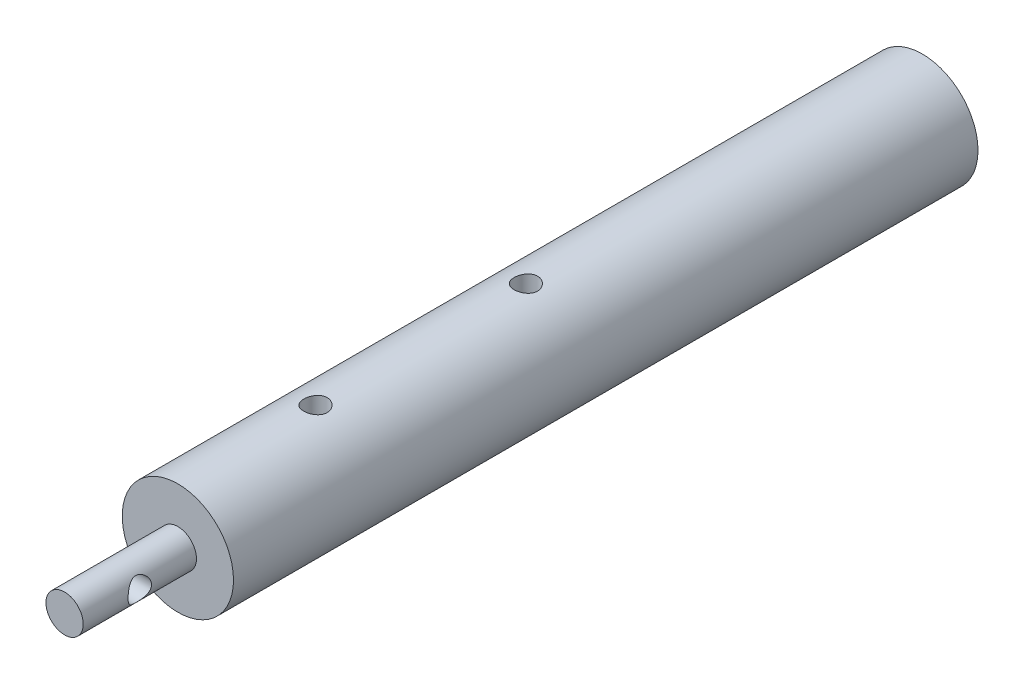
SolidWorks part; units mm, degrees
ref_plane "Front Plane" through (0, 0, 0) normal (0, 0, 1) x (1, 0, 0)
ref_plane "Top Plane" through (0, 0, 0) normal (0, 1, 0) x (1, 0, 0)
ref_plane "Right Plane" through (0, 0, 0) normal (1, 0, 0) x (0, 0, -1)
sketch "Sketch1" plane through (0, 0, 0) normal (0, 0, 1) x (1, 0, 0)
  circle A0 centre (0, 0) radius 8.7312
  dimension "D1" = 17.4625
extrude "Boss-Extrude1" add sketch "Sketch1" along normal blind 116.84
sketch "Sketch2" plane through (0, 0, 116.84) normal (0, 0, 1) x (1, 0, 0)
  circle A0 centre (0, 0) radius 2.921
  dimension "D1" = 5.842
extrude "Boss-Extrude2" add sketch "Sketch2" along normal blind 17.78
ref_plane "Plane1" through (0, 8.7312, 0) normal (0, 1, 0) x (1, 0, 0)
sketch "Sketch4" plane through (0, 8.7312, 0) normal (0, 1, 0) x (1, 0, 0)
  line L1 (-2.921, -134.62) -> (2.921, -134.62) construction
  circle A0 centre (0, -62.23) radius 1.8415
  circle A1 centre (0, -95.25) radius 1.8415
  dimension "D1" = 3.683
  dimension "D2" = 33.02
  dimension "D3" = 39.37
hole_wizard "#6-32 Tapped Hole1" positions "Sketch5" profile "Sketch6" tap size "#6-32" standard "ANSI Inch" end condition through all
sketch "Sketch5" plane through (0, 8.7312, 0) normal (0, 1, 0) x (1, 0, 0)
  point P0 (0, -62.23)
  point P3 (0, -95.25)
sketch "Sketch6" plane through (0, 8.7312, 62.23) normal (1, 0, 0) x (0, 0, 1)
  line L0 (0, 0) -> (0, 17.4625)
  line L1 (0, 17.4625) -> (1.3525, 17.4625)
  line L2 (1.3525, 17.4625) -> (1.3525, 0)
  line L5 (1.3525, 0) -> (0, 0)
  line L11 (0, -6.35) -> (0, 107.95) construction
  dimension "Thru Tap Drill Dia." = 2.7051
  dimension "Thru Tap Drill Depth" = 17.4625
cosmetic thread "Hole Thread1" parameters "D2"=3.5052
cosmetic thread "Hole Thread2" parameters "D2"=3.5052
ref_plane "Plane2" through (2.921, 0, 0) normal (1, 0, 0) x (0, 0, -1)
sketch "Sketch7" plane through (2.921, 0, 0) normal (1, 0, 0) x (0, 0, -1)
  line L1 (-134.62, 2.921) -> (-134.62, -2.921) construction
  circle A0 centre (-125.73, 0) radius 1.8415
  dimension "D1" = 3.683
  dimension "D2" = 8.89
hole_wizard "#6-32 Tapped Hole2" positions "Sketch8" profile "Sketch9" tap size "#6-32" standard "ANSI Inch" end condition through all
sketch "Sketch8" plane through (2.921, 0, 0) normal (1, 0, 0) x (0, 0, -1)
  point P0 (-125.73, 0)
sketch "Sketch9" plane through (2.921, 0, 125.73) normal (0, 1, 0) x (0, 0, -1)
  line L0 (0, 0) -> (0, 11.6522)
  line L1 (0, 11.6522) -> (1.3525, 11.6522)
  line L2 (1.3525, 11.6522) -> (1.3525, 0)
  line L5 (1.3525, 0) -> (0, 0)
  line L11 (0, -6.35) -> (0, 107.95) construction
  dimension "Thru Tap Drill Dia." = 2.7051
  dimension "Thru Tap Drill Depth" = 11.6522
cosmetic thread "Hole Thread3" parameters "D2"=3.5052
extrude "Cut-Extrude1" cut sketch "Sketch4" against normal through all
extrude "Cut-Extrude2" cut sketch "Sketch7" against normal through all
